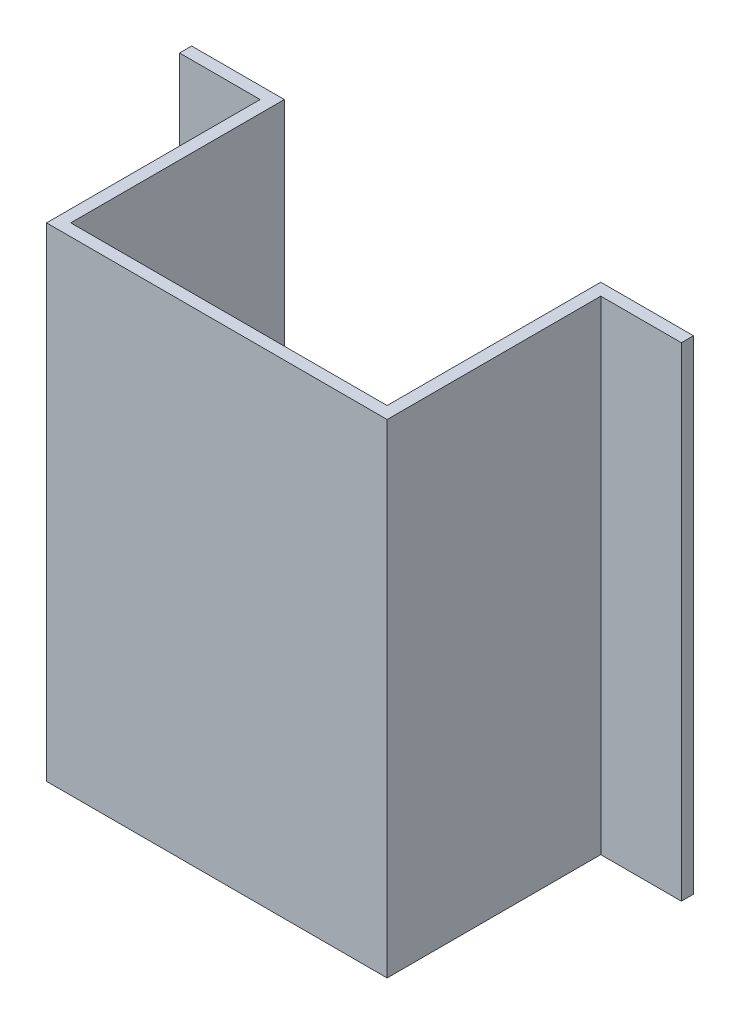
SolidWorks part; units mm, degrees
ref_plane "정면" through (0, 0, 0) normal (0, 0, 1) x (1, 0, 0)
ref_plane "윗면" through (0, 0, 0) normal (0, 1, 0) x (1, 0, 0)
ref_plane "우측면" through (0, 0, 0) normal (1, 0, 0) x (0, 0, -1)
sketch "스케치1" plane through (0, 0, 0) normal (0, 0, 1) x (1, 0, 0)
  line L1 (-42.25, 60) -> (42.25, 60)
  line L2 (-42.25, 60) -> (-42.25, -60)
  line L3 (-42.25, -60) -> (42.25, -60)
  line L4 (42.25, 60) -> (42.25, -60)
  line L5 (-42.25, 60) -> (42.25, -60) construction
  line L6 (-42.25, -60) -> (42.25, 60) construction
  point P0 (0, 0)
  dimension "D1" = 84.5
  dimension "D2" = 120
extrude "보스-돌출1" add sketch "스케치1" along normal blind 56
sketch "스케치2" plane through (0, 60, 0) normal (0, 1, 0) x (1, 0, 0)
  line L0 (42.25, 0) -> (-42.25, 0) construction
  line L1 (-39.25, 0) -> (39.25, 0)
  line L2 (-39.25, 0) -> (-39.25, -53)
  line L3 (-39.25, -53) -> (39.25, -53)
  line L4 (39.25, 0) -> (39.25, -53)
  line L5 (-42.25, -56) -> (-42.25, 0) construction
  line L6 (42.25, -56) -> (42.25, 0) construction
  line L7 (42.25, -56) -> (-42.25, -56) construction
  dimension "D1" = 3
  dimension "D2" = 3
  dimension "D3" = 3
extrude "컷-돌출1" cut sketch "스케치2" against normal through all
sketch "스케치3" plane through (-42.25, 0, 0) normal (-1, 0, 0) x (0, 0, 1)
  line L0 (56, -60) -> (0, -60) construction
  line L1 (0, 60) -> (3, 60)
  line L2 (0, 60) -> (0, -60)
  line L3 (0, -60) -> (3, -60)
  line L4 (3, 60) -> (3, -60)
  dimension "D1" = 3
extrude "보스-돌출2" add sketch "스케치3" along normal blind 20
mirror "대칭 복사1" about plane through (0, 0, 0) normal (1, 0, 0) of "보스-돌출2"
sketch "스케치4" plane through (0, 0, 56) normal (0, 0, 1) x (1, 0, 0)
  point P0 (0, 0)
